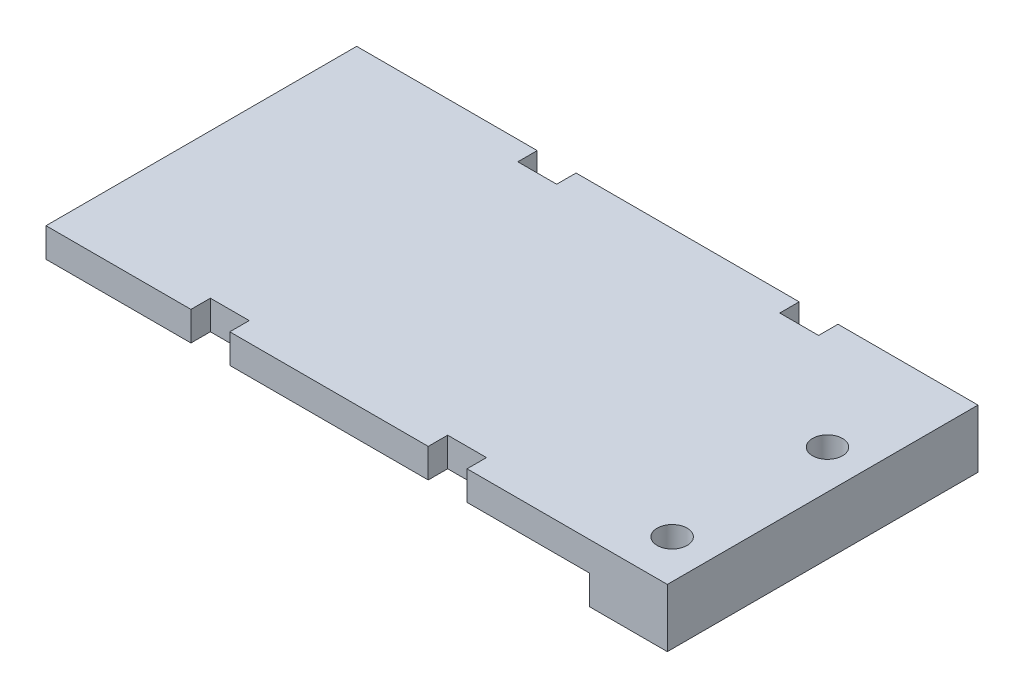
SolidWorks part; units mm, degrees
ref_plane "Front" through (0, 0, 0) normal (0, 0, 1) x (1, 0, 0)
ref_plane "Top" through (0, 0, 0) normal (0, 1, 0) x (1, 0, 0)
ref_plane "Right" through (0, 0, 0) normal (1, 0, 0) x (0, 0, -1)
sketch "Sketch1" plane through (0, 0, 0) normal (0, 1, 0) x (1, 0, 0)
  line L1 (-50.8, -25.4) -> (50.8, -25.4)
  line L2 (-50.8, -25.4) -> (-50.8, 25.4)
  line L3 (-50.8, 25.4) -> (50.8, 25.4)
  line L4 (50.8, -25.4) -> (50.8, 25.4)
  line L5 (-50.8, -25.4) -> (50.8, 25.4) construction
  line L6 (-50.8, 25.4) -> (50.8, -25.4) construction
  point P0 (0, 0)
  dimension "D1" = 101.6
  dimension "D2" = 50.8
extrude "Boss-Extrude1" add sketch "Sketch1" along normal blind 4.7625
sketch "Sketch3" plane through (0, 0, 0) normal (0, -1, 0) x (1, 0, 0)
  line L0 (50.8, -25.4) -> (-50.8, -25.4) construction
  line L1 (50.8, 25.4) -> (38.1, 25.4)
  line L2 (50.8, 25.4) -> (50.8, -25.4)
  line L3 (50.8, -25.4) -> (38.1, -25.4)
  line L4 (38.1, 25.4) -> (38.1, -25.4)
  dimension "D1" = 12.7
extrude "Boss-Extrude2" add sketch "Sketch3" along normal blind 4.7625
sketch "Sketch8" plane through (0, 4.7625, 0) normal (0, 1, 0) x (1, 0, 0)
  line L2 (50.8, 25.4) -> (-50.8, 25.4) construction
  line L4 (50.8, -25.4) -> (50.8, 25.4) construction
  point P0 (44.45, 7.1393)
  point P4 (44.45, -18.2607)
  point P19 (44.45, 4.4477)
  point P20 (44.45, 7.1393)
  dimension "D1" = 25.4
  dimension "D2" = 18.2607
  dimension "D3" = 6.35
hole_wizard "#10 (0.1935) Diameter Hole1" positions "Sketch8" profile "Sketch7" hole size "#10" standard "ANSI Inch" end condition through all
sketch "Sketch7" plane through (44.45, 4.7625, -7.1393) normal (1, 0, 0) x (0, 0, 1)
  line L0 (0, 0) -> (0, 9.525)
  line L1 (0, 9.525) -> (2.4574, 9.525)
  line L2 (2.4574, 9.525) -> (2.4574, 0)
  line L5 (2.4574, 0) -> (0, 0)
  line L11 (0, -6.35) -> (0, 107.95) construction
  dimension "Thru Hole Dia." = 4.9149
  dimension "Thru Hole Depth" = 9.525
sketch "Sketch9" plane through (0, 4.7625, 0) normal (0, 1, 0) x (1, 0, 0)
  line L14 (50.8, 25.4) -> (-50.8, 25.4) construction
  line L20 (21.5569, 25.4) -> (27.9069, 25.4)
  line L21 (21.5569, 25.4) -> (21.5569, 22.225)
  line L22 (21.5569, 22.225) -> (27.9069, 22.225)
  line L23 (27.9069, 25.4) -> (27.9069, 22.225)
  line L24 (-50.8, -25.4) -> (50.8, -25.4) construction
  line L25 (-21.2742, 25.4) -> (-14.9242, 25.4)
  line L26 (-21.2742, 25.4) -> (-21.2742, 22.225)
  line L27 (-21.2742, 22.225) -> (-14.9242, 22.225)
  line L28 (-14.9242, 25.4) -> (-14.9242, 22.225)
  line L29 (-27.0964, -25.4) -> (-20.7464, -25.4)
  line L30 (-27.0964, -25.4) -> (-27.0964, -22.225)
  line L31 (-27.0964, -22.225) -> (-20.7464, -22.225)
  line L32 (-20.7464, -25.4) -> (-20.7464, -22.225)
  line L34 (11.7031, -25.4) -> (18.0531, -25.4)
  line L35 (11.7031, -25.4) -> (11.7031, -22.225)
  line L36 (11.7031, -22.225) -> (18.0531, -22.225)
  line L37 (18.0531, -25.4) -> (18.0531, -22.225)
  line L38 (50.8, -25.4) -> (50.8, 25.4) construction
  dimension "D1" = 3.175
  dimension "D2" = 6.35
  dimension "D3" = 32.4495
  dimension "D4" = 77.8964
extrude "Cut-Extrude1" cut sketch "Sketch9" against normal through all
